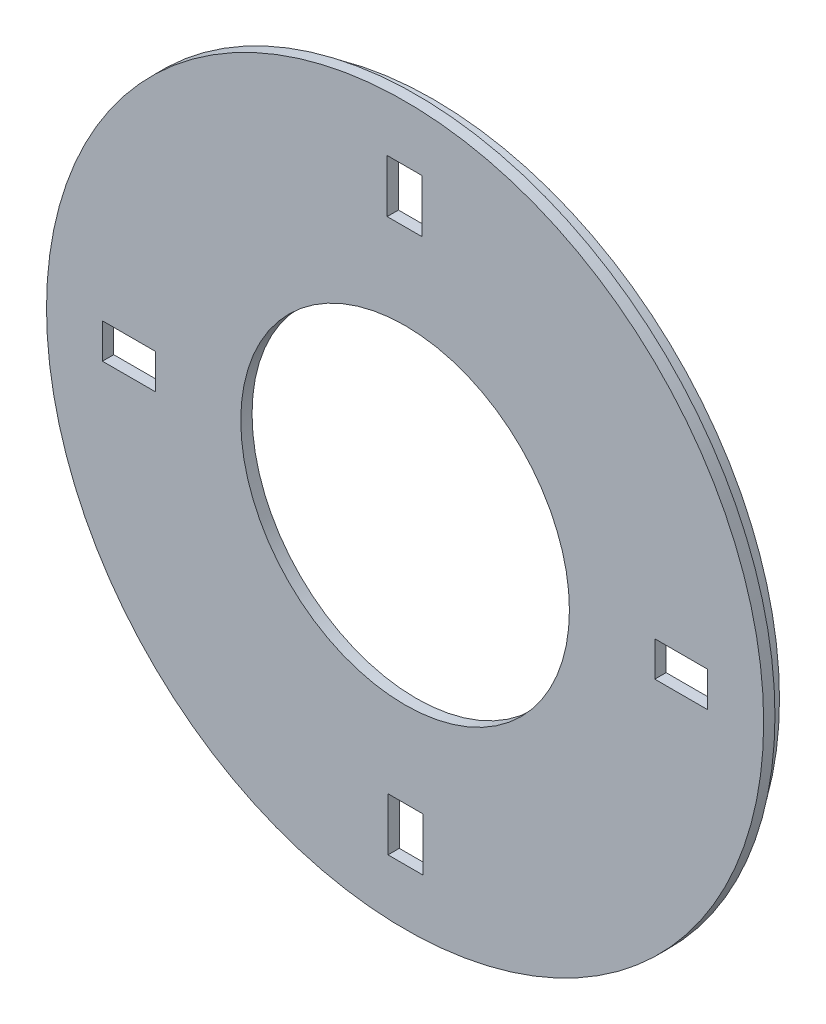
SolidWorks part; units mm, degrees
ref_plane "Front Plane" through (0, 0, 0) normal (1, 0, 0) x (0, 1, 0)
ref_plane "Top Plane" through (0, 0, 0) normal (0, 0, 1) x (0, 1, 0)
ref_plane "Right Plane" through (0, 0, 0) normal (0, 1, 0) x (-1, 0, 0)
sketch "Sketch1" plane through (0, 0, 0) normal (0, 0, 1) x (0, 1, 0)
  line L0 (53.5922, 3.1721) -> (53.5922, -3.0255)
  line L1 (-3.1721, 53.5922) -> (3.0255, 53.5922)
  line L2 (-3.1721, 53.5922) -> (-3.1721, 44.2196)
  line L3 (-3.1721, 44.2196) -> (3.0255, 44.2196)
  line L4 (3.0255, 53.5922) -> (3.0255, 44.2196)
  line L5 (-3.1721, 53.5922) -> (3.0255, 44.2196) construction
  line L6 (-3.1721, 44.2196) -> (3.0255, 53.5922) construction
  line L7 (53.5922, -3.0255) -> (44.2196, -3.0255)
  line L8 (53.5922, 3.1721) -> (44.2196, 3.1721)
  line L9 (44.2196, 3.1721) -> (44.2196, -3.0255)
  line L10 (3.1721, -53.5922) -> (-3.0255, -53.5922)
  line L11 (-3.0255, -53.5922) -> (-3.0255, -44.2196)
  line L12 (3.1721, -53.5922) -> (3.1721, -44.2196)
  line L13 (3.1721, -44.2196) -> (-3.0255, -44.2196)
  line L14 (-53.5922, -3.1721) -> (-53.5922, 3.0255)
  line L15 (-53.5922, 3.0255) -> (-44.2196, 3.0255)
  line L16 (-53.5922, -3.1721) -> (-44.2196, -3.1721)
  line L17 (-44.2196, -3.1721) -> (-44.2196, 3.0255)
  circle A0 centre (0, 0) radius 63.5
  circle A1 centre (0, 0) radius 29.1
  circle A2 centre (0, 0) radius 44.323 construction
  circle A3 centre (0, 0) radius 44.323 construction
  circle A4 centre (0, 0) radius 44.323 construction
  circle A5 centre (0, 0) radius 44.323 construction
  point P5 (-0.0733, 48.9059)
  point P28 (0, 0)
  dimension "D1" = 127
  dimension "D2" = 58.2
  dimension "D3" = 88.646
  dimension "D4" = 6.1976
  dimension "D5" = 9.3726
  dimension "D6" = 4
extrude "Boss-Extrude1" add sketch "Sketch1" along normal blind 2
sketch "Sketch2" plane through (0, 0, 0) normal (0, 0, -1) x (1, 0, 0)
  circle A1 centre (0, 0) radius 59.8
  circle A2 centre (0, 0) radius 61.3
  circle A3 centre (0, 0) radius 61.3
  dimension "D1" = 2.2
  dimension "D2" = 1.5
extrude "Boss-Extrude2" add sketch "Sketch2" along normal blind 3
equation "\"w\"= 3 / 8in"
equation "\"h\"= 1 / 4in"
equation "\"k\"= 0.006in"
equation "\"wk\"= \"w\" - \"k\""
equation "\"hk\"= \"h\" - \"k\""
equation "\"D4@Sketch1\"=\"hk\""
equation "\"D5@Sketch1\"=\"wk\""
